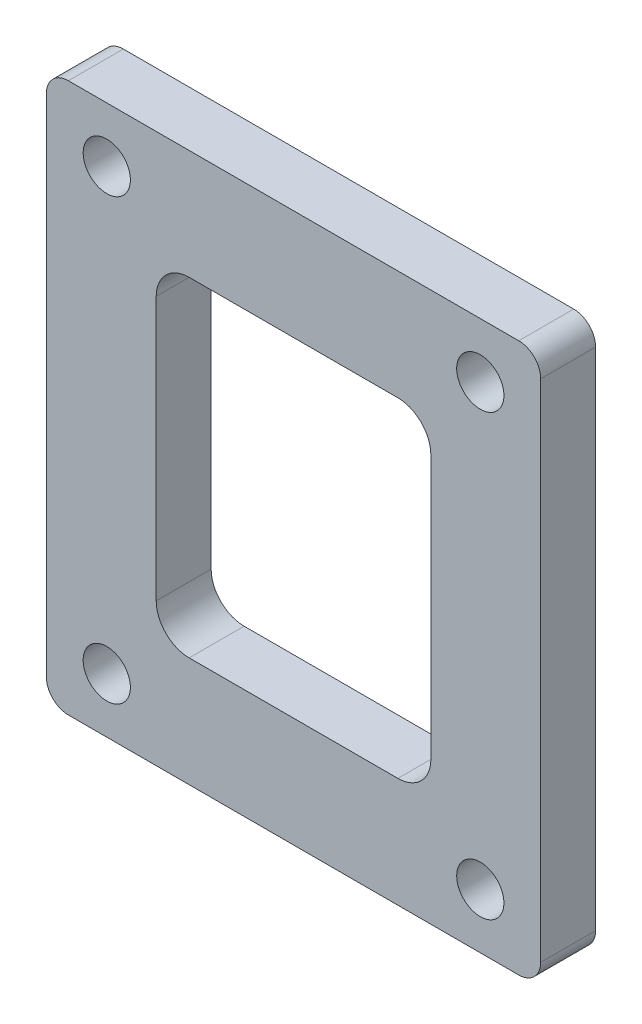
SolidWorks part; units mm, degrees
material "5052-H34"
ref_plane "正面" through (0, 0, 0) normal (0, 0, 1) x (1, 0, 0)
ref_plane "平面" through (0, 0, 0) normal (0, 1, 0) x (1, 0, 0)
ref_plane "右側面" through (0, 0, 0) normal (1, 0, 0) x (0, 0, -1)
sketch "ｽｹｯﾁ1" plane through (0, 0, 0) normal (0, 0, 1) x (1, 0, 0)
  line L0 (22.5, 50) -> (22.5, 0) construction
  line L1 (0, 0) -> (45, 0)
  line L2 (0, 0) -> (0, 50)
  line L3 (0, 50) -> (45, 50)
  line L4 (45, 0) -> (45, 50)
  line L5 (45, 25) -> (0, 25) construction
  line L7 (10, 10) -> (35, 10)
  line L8 (10, 10) -> (10, 40)
  line L9 (10, 40) -> (35, 40)
  line L10 (35, 10) -> (35, 40)
  line L11 (10, 10) -> (35, 40) construction
  line L12 (10, 40) -> (35, 10) construction
  circle A0 centre (5.5, 5) radius 2.15
  circle A1 centre (5.5, 45) radius 2.15
  circle A2 centre (39.5, 5) radius 2.15
  circle A3 centre (39.5, 45) radius 2.15
  point P17 (22.5, 25)
  dimension "D3" = 5.5
  dimension "D4" = 5
  dimension "D5" = 4.3
  dimension "D1" = 45
  dimension "D2" = 50
  dimension "D6" = 25
  dimension "D7" = 10
extrude "ﾎﾞｽ - 押し出し1" add sketch "ｽｹｯﾁ1" along normal blind 5
fillet "ﾌｨﾚｯﾄ1" radius 2 4 edges at (45, 0, 2.5) (0, 0, 2.5) (45, 50, 2.5) (0, 50, 2.5)
fillet "ﾌｨﾚｯﾄ2" radius 3 4 edges at (10, 10, 2.5) (35, 10, 2.5) (35, 40, 2.5) (10, 40, 2.5)
